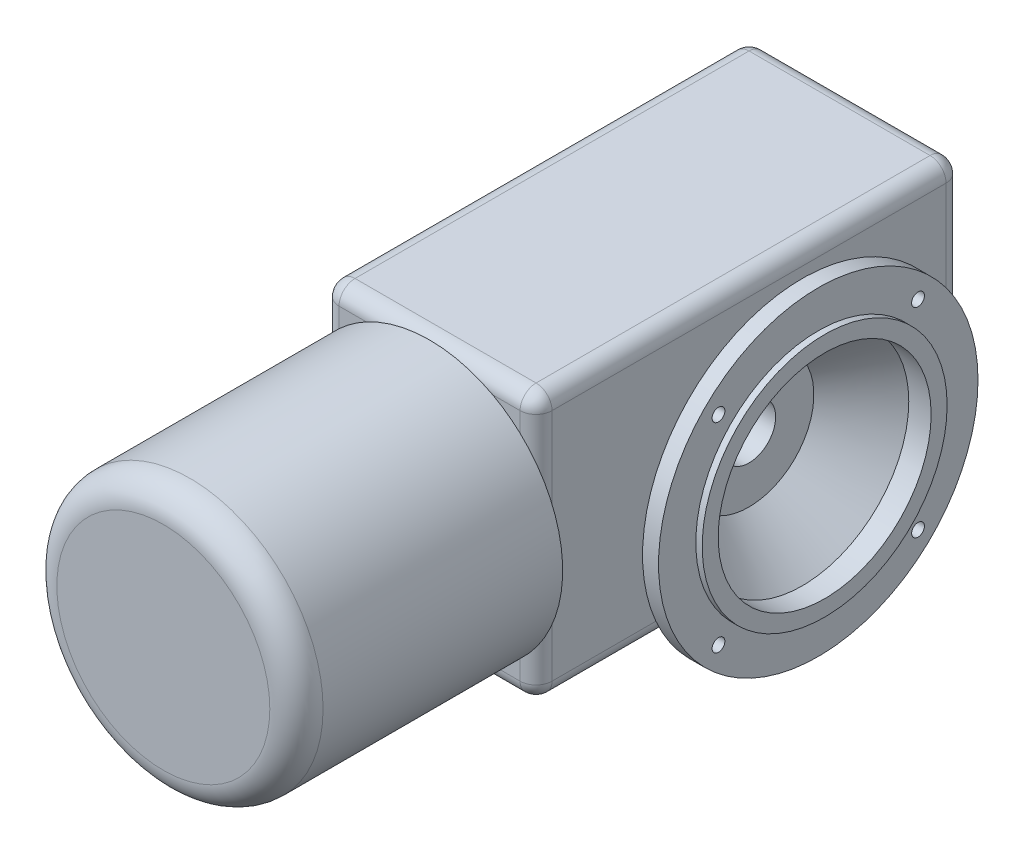
SolidWorks part; units mm, degrees
ref_plane "前视基准面" through (0, 0, 0) normal (0, 0, 1) x (1, 0, 0)
ref_plane "上视基准面" through (0, 0, 0) normal (0, 1, 0) x (1, 0, 0)
ref_plane "右视基准面" through (0, 0, 0) normal (1, 0, 0) x (0, 0, -1)
sketch "草图4" plane through (0, 0, 0) normal (1, 0, 0) x (0, 0, -1)
  line L0 (0, -1000) -> (0, 49000) construction
  line L1 (-200, 125) -> (200, 125)
  line L2 (-200, 125) -> (-200, -125)
  line L3 (-200, -125) -> (200, -125)
  line L4 (200, 125) -> (200, -125)
  line L5 (-1000, 0) -> (49000, 0) construction
  dimension "D1" = 400
  dimension "D2" = 250
extrude "凸台-拉伸4" add sketch "草图4" against normal blind 200
sketch "草图10" plane through (0, 0, 0) normal (1, 0, 0) x (0, 0, -1)
  circle A0 centre (0, 0) radius 25
  dimension "D1" = 50
extrude "切除-拉伸1" cut sketch "草图10" against normal blind 180
fillet "圆角3" radius 15 12 edges at (-100, -125, 200) (-200, -125, 0) (-200, 0, -200) (-100, 125, -200) (0, 125, 0) (0, 0, 200) (-100, 125, 200) (-200, 0, 200) (-200, 125, 0) (0, -125, 0) (-100, -125, -200) (0, 0, -200)
sketch "草图9" plane through (0, 0, 200) normal (0, 0, 1) x (1, 0, 0)
  line L0 (-1185, 0) -> (48815, 0) construction
  line L1 (-185, 110) -> (-185, -110) construction
  line L2 (-100, -890) -> (-100, 49110) construction
  line L3 (-15, 110) -> (-185, 110) construction
  circle A0 centre (-100, 0) radius 125
  point P5 (-185, 0)
  point P10 (-100, 110)
  dimension "D1" = 250
extrude "凸台-拉伸8" add sketch "草图9" along normal blind 250
fillet "圆角4" radius 25 1 edges at (25, 0, 450)
sketch "草图12" plane through (0, 0, 0) normal (0, 0, 1) x (1, 0, 0)
  line L0 (0, 75) -> (50, 125)
  line L1 (0, 110) -> (0, -110) construction
  line L2 (50, 125) -> (50, 110.8579)
  line L3 (0, 75) -> (0, 60.8579)
  line L4 (0, 60.8579) -> (50, 110.8579)
  line L5 (-1000, 0) -> (49000, 0) construction
  circle A0 centre (-100, 0) radius 125 construction
  dimension "D1" = 125
  dimension "D2" = 10
  dimension "D3" = 50
revolve "旋转1" add sketch "草图12" angle 360 about L5
sketch "草图5" plane through (50, 0, 0) normal (1, 0, 0) x (0, 0, -1)
  circle A0 centre (0, 0) radius 100
  circle A1 centre (0, 0) radius 150
  dimension "D1" = 300
  dimension "D2" = 200
extrude "凸台-拉伸5" add sketch "草图5" along normal blind 15
sketch "草图6" plane through (65, 0, 0) normal (1, 0, 0) x (0, 0, -1)
  circle A0 centre (0, 0) radius 100
  circle A1 centre (0, 0) radius 115
  circle A2 centre (0, 0) radius 100 construction
  dimension "D1" = 230
extrude "凸台-拉伸6" add sketch "草图6" along normal blind 6
sketch "草图13" plane through (65, 0, 0) normal (1, 0, 0) x (0, 0, -1)
  line L0 (-1000, 0) -> (49000, 0) construction
  line L1 (0, -1000) -> (0, 49000) construction
  line L2 (0, 0) -> (35355.3391, 35355.3391) construction
  line L3 (0, 0) -> (-35355.3391, 35355.3391) construction
  circle A0 centre (93.6916, 93.6916) radius 6
  circle A1 centre (-93.6916, -93.6916) radius 6
  circle A2 centre (-93.6916, 93.6916) radius 6
  circle A3 centre (93.6916, -93.6916) radius 6
  dimension "D2" = 12
  dimension "D1" = 45
  dimension "D3" = 265
  dimension "D4" = 265
extrude "切除-拉伸2" cut sketch "草图13" against normal blind 15
